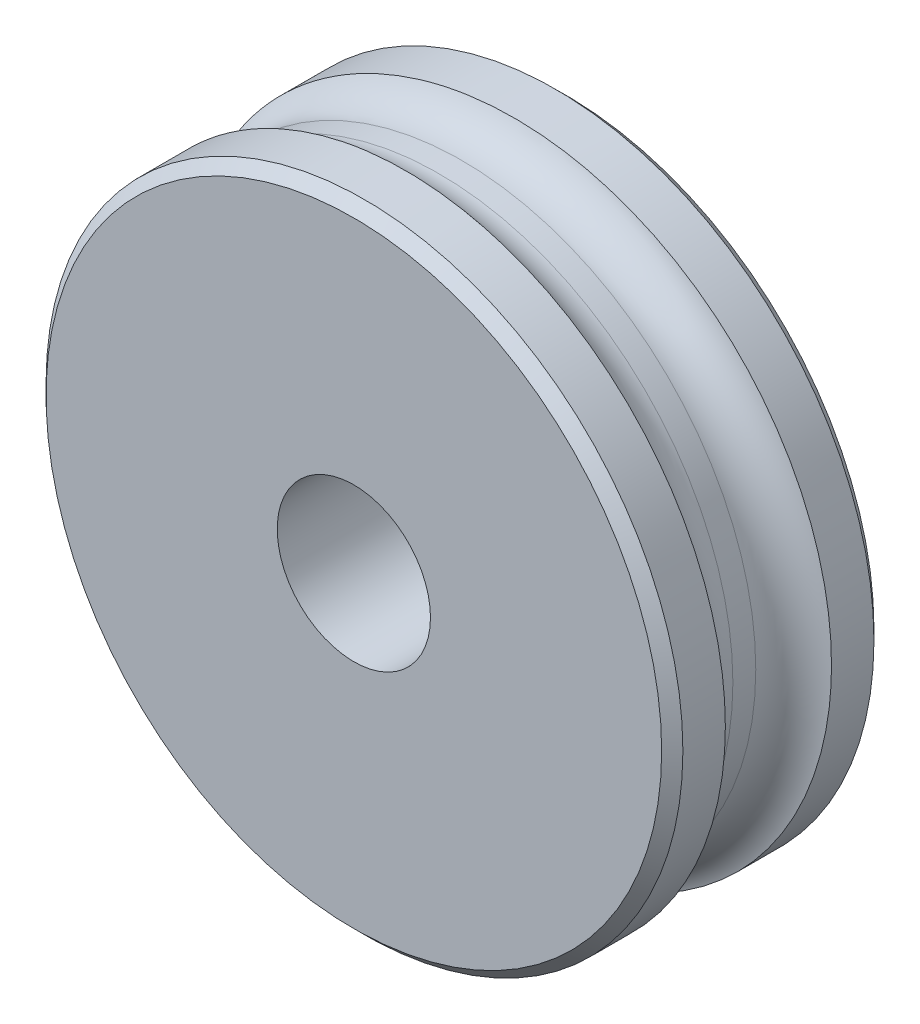
SolidWorks part; units mm, degrees
ref_plane "前视基准面" through (0, 0, 0) normal (0, 0, 1) x (1, 0, 0)
ref_plane "上视基准面" through (0, 0, 0) normal (0, 1, 0) x (1, 0, 0)
ref_plane "右视基准面" through (0, 0, 0) normal (1, 0, 0) x (0, 0, -1)
other "Configuration Table"
sketch "草图1" plane through (0, 0, 70.26) normal (0, 0, 1) x (1, 0, 0)
  circle A0 centre (-297.6709, 626.4154) radius 14.4381
  circle A1 centre (-297.6709, 626.4154) radius 60
extrude "凸台-拉伸1" add sketch "草图1" against normal up to surface (40 mm away)
ref_plane "基准面1" through (0, 0, 50.26) normal (0, 0, 1) x (1, 0, 0)
sketch "草图3" plane through (0, 0, 0) normal (0, 0, 1) x (1, 0, 0)
  point P0 (-297.6709, 626.4154)
ref_plane "基准面2" through (0, 626.4154, 0) normal (0, 1, 0) x (1, 0, 0)
sketch "草图4" plane through (0, 626.4154, 0) normal (0, 1, 0) x (1, 0, 0)
  line L0 (-316.0681, -48.1033) -> (-244.0953, -48.1033) construction
  line L1 (-244.0953, -48.1033) -> (-244.0953, -52.4167)
  line L2 (-237.6709, -40.26) -> (-237.6709, -60.26)
  line L3 (-299.4917, -70.26) -> (-299.4917, -4.8999) construction
  line L4 (-357.6709, -70.26) -> (-237.6709, -70.26) construction
  arc A0 (-237.6709, -40.26) -> (-244.0953, -48.1033) centre (-236.0953, -48.1033) ccw
  arc A1 (-237.6709, -40.26) -> (-244.0953, -48.1033) centre (-236.0953, -48.1033) ccw construction
  arc A2 (-237.6709, -60.26) -> (-244.0953, -52.4167) centre (-236.0953, -52.4167) cw
revolve "切除-旋转1" cut sketch "草图4" angle 360 about L3
chamfer "倒角1" distance 2 angle 45 2 edges at (-237.6709, 626.4154, 30.26) (-237.6709, 626.4154, 70.26)
